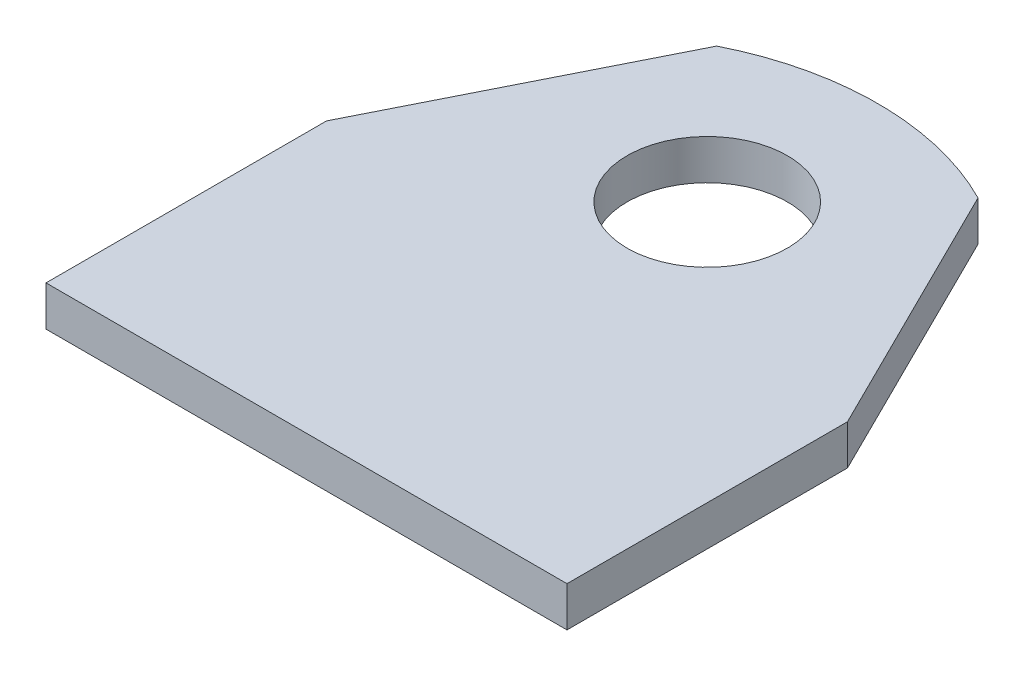
SolidWorks part; units mm, degrees
ref_plane "Front Plane" through (0, 0, 0) normal (0, 0, 1) x (1, 0, 0)
ref_plane "Top Plane" through (0, 0, 0) normal (0, 1, 0) x (1, 0, 0)
ref_plane "Right Plane" through (0, 0, 0) normal (1, 0, 0) x (0, 0, -1)
sketch "Sketch1" plane through (0, 0, 0) normal (0, 1, 0) x (1, 0, 0)
  line L0 (0, 0) -> (65, 0)
  line L1 (0, 0) -> (0, 35)
  line L2 (65, 0) -> (65, 35)
  line L3 (0, 35) -> (16.2524, 67.4271)
  line L4 (65, 35) -> (48.9067, 67.4271)
  line L5 (0, 35) -> (65, 35)
  line L6 (32.5, 35) -> (32.5, 50)
  arc A0 (16.2524, 67.4271) -> (48.96, 67.3198) centre (32.5, 35) cw
  circle A1 centre (32.5, 50) radius 10
extrude "Boss-Extrude1" add sketch "Sketch1" along normal blind 5
